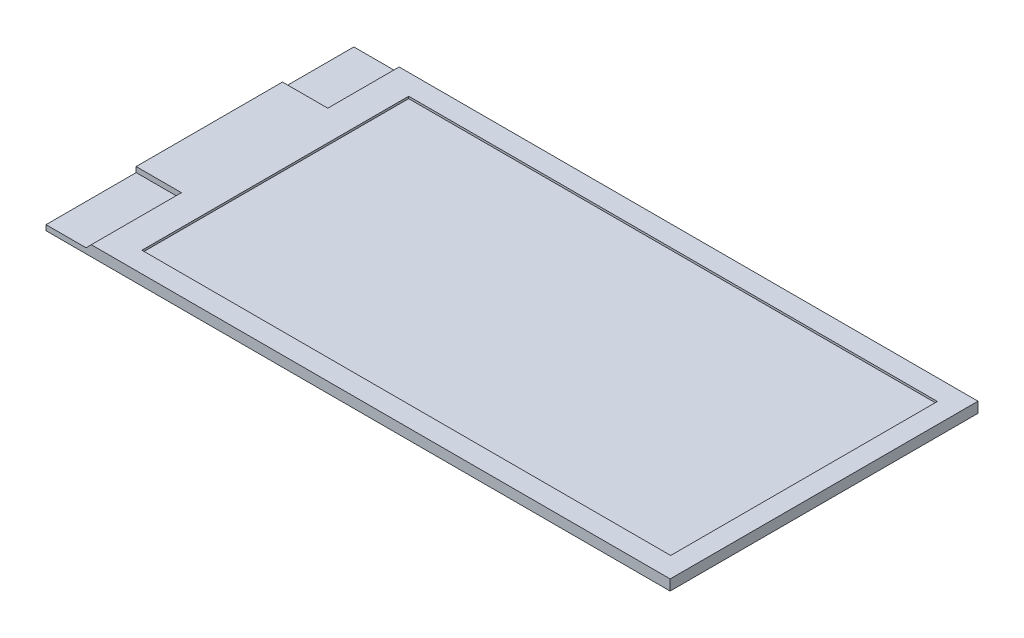
SolidWorks part; units mm, degrees
ref_plane "Front Plane" through (0, 0, 0) normal (0, 0, 1) x (1, 0, 0)
ref_plane "Top Plane" through (0, 0, 0) normal (0, 1, 0) x (1, 0, 0)
ref_plane "Right Plane" through (0, 0, 0) normal (1, 0, 0) x (0, 0, -1)
sketch "Sketch1" plane through (0, 0, 0) normal (0, 1, 0) x (1, 0, 0)
  line L1 (-29.6, 14.6) -> (29.6, 14.6)
  line L2 (-29.6, 14.6) -> (-29.6, -14.6)
  line L3 (-29.6, -14.6) -> (29.6, -14.6)
  line L4 (29.6, 14.6) -> (29.6, -14.6)
  line L5 (-29.6, 14.6) -> (29.6, -14.6) construction
  line L6 (-29.6, -14.6) -> (29.6, 14.6) construction
  point P0 (0, 0)
  dimension "D1" = 59.2
  dimension "D2" = 29.2
extrude "Boss-Extrude1" add sketch "Sketch1" along normal blind 1
sketch "Sketch2" plane through (0, 1, 0) normal (0, 1, 0) x (1, 0, 0)
  line L0 (29.6, -14.6) -> (29.6, 14.6) construction
  line L1 (-22.45, 12.65) -> (27.7, 12.65)
  line L2 (-22.45, 12.65) -> (-22.45, -12.65)
  line L3 (-22.45, -12.65) -> (27.7, -12.65)
  line L4 (27.7, 12.65) -> (27.7, -12.65)
  line L5 (-22.45, 12.65) -> (27.7, -12.65) construction
  line L6 (-22.45, -12.65) -> (27.7, 12.65) construction
  line L7 (0, 0) -> (5.25, 0) construction
  point P0 (2.625, 0)
  point P10 (0, 0)
  dimension "D1" = 50.15
  dimension "D2" = 1.9
  dimension "D3" = 25.3
extrude "Cut-Extrude1" cut sketch "Sketch2" against normal blind 0.2
sketch "Sketch3" plane through (0, 0, 14.6) normal (0, 0, 1) x (1, 0, 0)
  line L0 (-29.6, 0.5) -> (-25.8041, 0.5)
  line L1 (-29.6, 1) -> (-29.6, 0) construction
  line L2 (-25.8041, 0.5) -> (-25.3041, 1)
  line L3 (-29.6, 1) -> (29.6, 1) construction
  line L4 (-25.3041, 1) -> (-29.6, 1)
  line L5 (-29.6, 1) -> (-29.6, 0.5)
extrude "Cut-Extrude2" cut sketch "Sketch3" against normal through all
sketch "Sketch4" plane through (-29.6, 0, 0) normal (-1, 0, 0) x (0, 0, 1)
  line L0 (-14.6, 1) -> (14.6, 1) construction
  line L1 (-7.83, 1) -> (6.05, 1)
  line L2 (-7.83, 1) -> (-7.83, 0.2929)
  line L3 (-7.83, 0.2929) -> (6.05, 0.2929)
  line L4 (6.05, 1) -> (6.05, 0.2929)
  line L5 (-14.6, 0.5) -> (-14.6, 1) construction
  dimension "D1" = 6.77
  dimension "D2" = 13.88
extrude "Boss-Extrude2" add sketch "Sketch4" against normal blind 4.5
